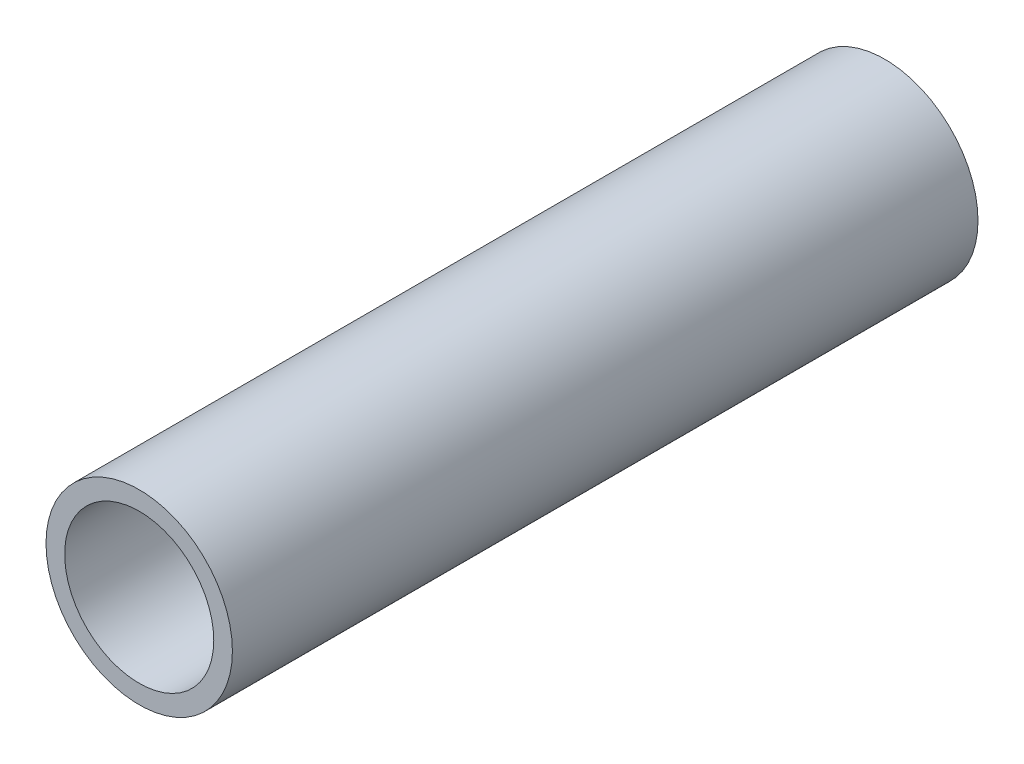
SolidWorks part; units mm, degrees
ref_plane "Plano frontal" through (0, 0, 0) normal (0, 0, 1) x (1, 0, 0)
ref_plane "Plano superior" through (0, 0, 0) normal (0, 1, 0) x (1, 0, 0)
ref_plane "Plano direito" through (0, 0, 0) normal (1, 0, 0) x (0, 0, -1)
sketch "Esboço1" plane through (0, 0, 0) normal (0, 0, 1) x (1, 0, 0)
  circle A0 centre (0, 0) radius 12.5
  circle A1 centre (0, 0) radius 10
  dimension "D1" = 25
  dimension "D2" = 20
extrude "Ressalto-extrusão1" add sketch "Esboço1" along normal blind 100
